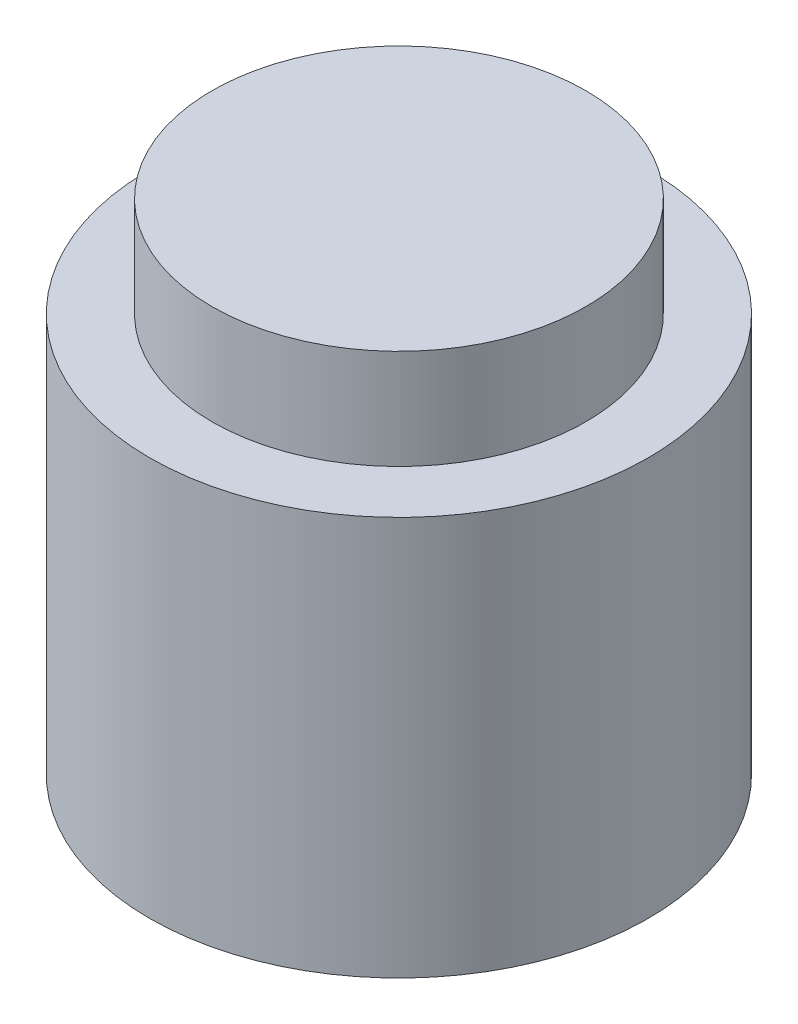
SolidWorks part; units mm, degrees
ref_plane "Front Plane" through (0, 0, 0) normal (0, 0, 1) x (1, 0, 0)
ref_plane "Top Plane" through (0, 0, 0) normal (0, 1, 0) x (1, 0, 0)
ref_plane "Right Plane" through (0, 0, 0) normal (1, 0, 0) x (0, 0, -1)
sketch "Sketch1" plane through (0, 0, 0) normal (0, 1, 0) x (1, 0, 0)
  line L0 (-2.4367, 1.75) -> (2.4367, 1.75)
  line L1 (-2.4367, -1.75) -> (2.4367, -1.75)
  circle A0 centre (0, 0) radius 3
  circle A1 centre (0, 0) radius 5
  dimension "D1" = 6
  dimension "D4" = 10
  dimension "D2" = 3.5
  dimension "D3" = 1.75
extrude "Boss-Extrude1" add sketch "Sketch1" along normal blind 6 contours L0 A0 | L1 A0 | A1 A0
sketch "Sketch5" plane through (0, 6, 0) normal (0, 1, 0) x (1, 0, 0)
  circle A0 centre (0, 0) radius 5
extrude "Boss-Extrude5" add sketch "Sketch5" along normal blind 2
sketch "Sketch7" plane through (0, 8, 0) normal (0, 1, 0) x (1, 0, 0)
  circle A0 centre (0, 0) radius 3.75
  dimension "D1" = 7.5
extrude "Boss-Extrude6" add sketch "Sketch7" along normal blind 2
